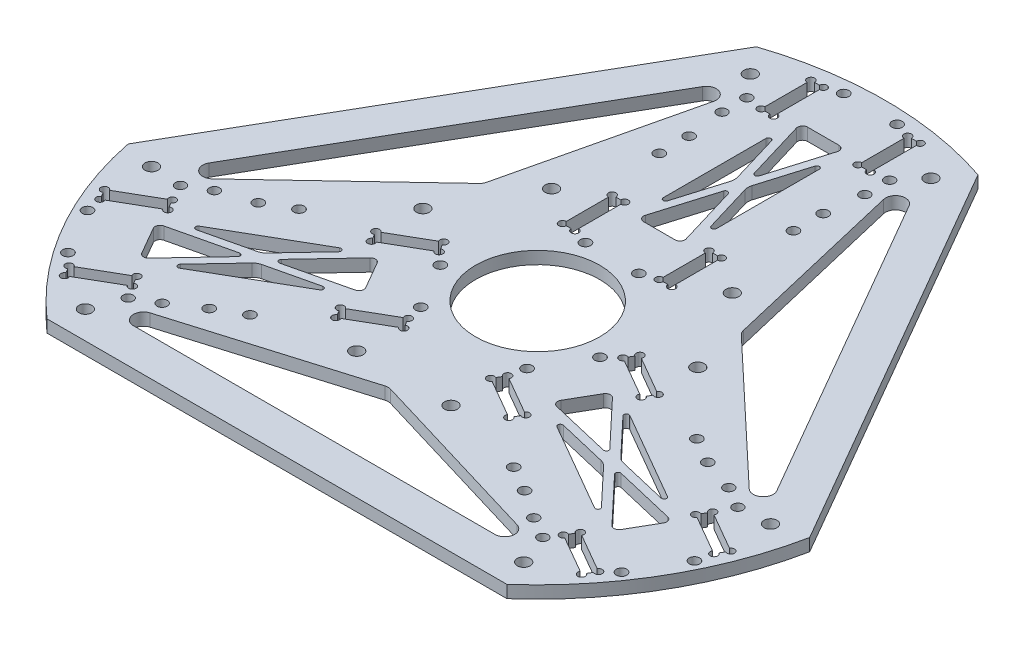
SolidWorks part; units mm, degrees
ref_plane "前视基准面" through (0, 0, 0) normal (0, 0, 1) x (1, 0, 0)
ref_plane "上视基准面" through (0, 0, 0) normal (0, 1, 0) x (1, 0, 0)
ref_plane "右视基准面" through (0, 0, 0) normal (1, 0, 0) x (0, 0, -1)
sketch "草图1" plane through (0, 0, 0) normal (0, 1, 0) x (1, 0, 0)
  line L0 (0, 0) -> (0, 50000) construction
  line L1 (0, 0) -> (-43301.2702, 25000) construction
  line L2 (-0.5416, -0.3127) -> (43300.7286, 24999.6873) construction
  line L3 (-34.641, 150) -> (-147.2243, -45)
  line L4 (34.641, 150) -> (147.2243, -45)
  line L5 (112.5833, -105) -> (-112.5833, -105)
  arc A0 (34.641, 150) -> (-34.641, 150) centre (0, 130) ccw
  arc A1 (-147.2243, -45) -> (-112.5833, -105) centre (-112.5833, -65) ccw
  arc A3 (147.2243, -45) -> (112.5833, -105) centre (112.5833, -65) cw
  dimension "D6" = 80
  dimension "D1" = 60
  dimension "D2" = 60
  dimension "D3" = 130
  dimension "D5" = 130
extrude "凸台-拉伸1" add sketch "草图1" along normal blind 5
sketch "草图2" plane through (0, 5, 0) normal (0, 1, 0) x (1, 0, 0)
  line L0 (0, 0) -> (0, 50000) construction
  line L1 (-10.75, 134) -> (-10.75, 30) construction
  line L2 (-10.75, 82) -> (49989.25, 82) construction
  line L3 (-22, 52) -> (-17, 52)
  line L4 (-22, 132) -> (-17, 132)
  line L5 (-22, 132) -> (-22, 112)
  line L6 (-22, 112) -> (-17, 112)
  line L7 (-17, 132) -> (-17, 112)
  line L8 (-17, 32) -> (-17, 52)
  line L9 (-22, 32) -> (-17, 32)
  line L10 (-22, 32) -> (-22, 52)
  line L11 (22, 32) -> (22, 52)
  line L12 (22, 32) -> (17, 32)
  line L13 (17, 32) -> (17, 52)
  line L14 (22, 52) -> (17, 52)
  line L15 (22, 112) -> (17, 112)
  line L16 (17, 132) -> (17, 112)
  line L17 (22, 132) -> (17, 132)
  line L18 (22, 132) -> (22, 112)
  circle A0 centre (-10.75, 30) radius 2.1
  circle A1 centre (-10.75, 134) radius 2.1
  circle A2 centre (10.75, 30) radius 2.1
  circle A3 centre (10.75, 134) radius 2.1
  circle A4 centre (-36.38, 42) radius 2.6
  circle A5 centre (-36.38, 122) radius 2.6
  circle A6 centre (36.38, 122) radius 2.6
  circle A7 centre (36.38, 42) radius 2.6
  circle A8 centre (-27, 88) radius 2.1
  circle A9 centre (-27, 76) radius 2.1
  circle A10 centre (27, 76) radius 2.1
  circle A11 centre (27, 88) radius 2.1
  point P15 (-10.75, 82)
  dimension "D1" = 4.2
  dimension "D6" = 5.2
  dimension "D8" = 4.2
  dimension "D2" = 21.5
  dimension "D3" = 104
  dimension "D4" = 30
  dimension "D5" = 80
  dimension "D7" = 36.38
  dimension "D9" = 27
  dimension "D10" = 6
  dimension "D11" = 5
  dimension "D12" = 5
  dimension "D13" = 20
  dimension "D14" = 30
extrude "切除-拉伸1" cut sketch "草图2" against normal blind 10
pattern_circular "阵列(圆周)1" count 3 over 360 about axis through (0, 0, 0.9148) along (0, 1, 0) of "切除-拉伸1"
sketch "草图3" plane through (0, 5, 0) normal (0, 1, 0) x (1, 0, 0)
  line L0 (-72.7463, -90) -> (72.7463, -90)
  line L1 (73.8956, -82.1687) -> (1.1494, -60.3448)
  line L2 (-1.1494, -60.3448) -> (-73.8956, -82.1687)
  line L3 (0, 0) -> (0, 50000) construction
  line L4 (-51.6854, 31.1678) -> (-34.2124, 105.0799)
  line L5 (-41.5692, 108.0001) -> (-114.3154, -18.0001)
  line L6 (-108.108, -22.9112) -> (-52.8348, 29.177)
  line L7 (52.8348, 29.177) -> (108.108, -22.9112)
  line L8 (114.3154, -18.0001) -> (41.5692, 108.0001)
  line L9 (34.2124, 105.0799) -> (51.6854, 31.1678)
  arc A0 (52.8348, 29.177) -> (51.6854, 31.1678) centre (55.5782, 32.0881) cw
  arc A1 (114.3154, -18.0001) -> (108.108, -22.9112) centre (110.8513, -20.0001) cw
  arc A2 (41.5692, 108.0001) -> (34.2124, 105.0799) centre (38.1051, 106.0001) ccw
  arc A3 (1.1494, -60.3448) -> (-1.1494, -60.3448) centre (0, -64.1761) ccw
  arc A4 (72.7463, -90) -> (73.8956, -82.1687) centre (72.7463, -86) ccw
  arc A5 (-72.7463, -90) -> (-73.8956, -82.1687) centre (-72.7463, -86) cw
  arc A6 (-108.108, -22.9112) -> (-114.3154, -18.0001) centre (-110.8513, -20.0001) cw
  arc A7 (-34.2124, 105.0799) -> (-41.5692, 108.0001) centre (-38.1051, 106.0001) ccw
  arc A8 (-51.6854, 31.1678) -> (-52.8348, 29.177) centre (-55.5782, 32.0881) cw
  point P15 (0, 0)
  point P23 (0, -60)
  point P26 (100, -90)
  point P29 (-100, -90)
  dimension "D1" = 200
  dimension "D5" = 4
  dimension "D2" = 30
  dimension "D3" = 60
  dimension "D4" = 3
extrude "切除-拉伸2" cut sketch "草图3" against normal blind 10
sketch "草图4" plane through (0, 5, 0) normal (0, 1, 0) x (1, 0, 0)
  line L0 (0, 0) -> (0, 50000) construction
  line L5 (-6.3119, 115) -> (6.3119, 115)
  line L6 (8.2276, 112.4253) -> (0.9578, 88.1928)
  line L7 (-0.9578, 88.1928) -> (-8.2276, 112.4253)
  line L8 (-10.75, 30) -> (-10.75, 134) construction
  line L9 (-10.75, 82) -> (49989.25, 82) construction
  line L10 (8.2276, 51.5747) -> (0.9578, 75.8072)
  line L11 (-6.3119, 49) -> (6.3119, 49)
  line L12 (-0.9578, 75.8072) -> (-8.2276, 51.5747)
  line L13 (-10.75, 102.6866) -> (-10.75, 61.3134)
  line L14 (-8.7922, 61.0261) -> (-2.931, 80.5633)
  line L15 (-8.7922, 102.9739) -> (-2.931, 83.4367)
  line L16 (10.75, 102.6866) -> (10.75, 61.3134)
  line L17 (8.7922, 61.0261) -> (2.931, 80.5633)
  line L18 (8.7922, 102.9739) -> (2.931, 83.4367)
  line L19 (93.5741, -43.8727) -> (73.7238, -39.18)
  line L20 (57.2462, -22.8988) -> (71.2353, -37.7433)
  line L21 (94.3042, -42.0335) -> (58.474, -21.3469)
  line L22 (40.5512, -32.9127) -> (65.1721, -38.7331)
  line L23 (66.1299, -37.0741) -> (48.7788, -18.662)
  line L24 (45.5912, -19.0337) -> (39.2793, -29.9663)
  line L25 (83.5542, -60.6531) -> (47.724, -39.9665)
  line L26 (48.4541, -38.1273) -> (68.3043, -42.82)
  line L27 (84.7819, -59.1012) -> (70.7928, -44.2567)
  line L28 (76.8561, -43.2669) -> (101.477, -49.0873)
  line L29 (102.7489, -52.0337) -> (96.437, -62.9663)
  line L30 (93.2494, -63.338) -> (75.8983, -44.9259)
  line L31 (-84.7819, -59.1012) -> (-70.7928, -44.2567)
  line L32 (-48.4541, -38.1273) -> (-68.3043, -42.82)
  line L33 (-83.5542, -60.6531) -> (-47.724, -39.9665)
  line L34 (-48.7788, -18.662) -> (-66.1299, -37.0741)
  line L35 (-65.1721, -38.7331) -> (-40.5512, -32.9127)
  line L36 (-39.2793, -29.9663) -> (-45.5912, -19.0337)
  line L37 (-94.3042, -42.0335) -> (-58.474, -21.3469)
  line L38 (-57.2462, -22.8988) -> (-71.2353, -37.7433)
  line L39 (-93.5741, -43.8727) -> (-73.7238, -39.18)
  line L40 (-75.8983, -44.9259) -> (-93.2494, -63.338)
  line L41 (-96.437, -62.9663) -> (-102.7489, -52.0337)
  line L42 (-101.477, -49.0873) -> (-76.8561, -43.2669)
  arc A0 (2.931, 80.5633) -> (2.931, 83.4367) centre (7.7202, 82) cw
  arc A1 (-2.931, 80.5633) -> (-2.931, 83.4367) centre (-7.7202, 82) ccw
  arc A2 (-10.75, 61.3134) -> (-8.7922, 61.0261) centre (-9.75, 61.3134) ccw
  arc A3 (-8.7922, 102.9739) -> (-10.75, 102.6866) centre (-9.75, 102.6866) ccw
  arc A4 (10.75, 61.3134) -> (8.7922, 61.0261) centre (9.75, 61.3134) cw
  arc A5 (10.75, 102.6866) -> (8.7922, 102.9739) centre (9.75, 102.6866) ccw
  arc A6 (0.9578, 75.8072) -> (-0.9578, 75.8072) centre (0, 75.5199) ccw
  arc A7 (0.9578, 88.1928) -> (-0.9578, 88.1928) centre (0, 88.4801) cw
  arc A8 (6.3119, 49) -> (8.2276, 51.5747) centre (6.3119, 51) ccw
  arc A9 (-6.3119, 49) -> (-8.2276, 51.5747) centre (-6.3119, 51) cw
  arc A10 (8.2276, 112.4253) -> (6.3119, 115) centre (6.3119, 113) ccw
  arc A11 (-8.2276, 112.4253) -> (-6.3119, 115) centre (-6.3119, 113) cw
  arc A12 (93.5741, -43.8727) -> (94.3042, -42.0335) centre (93.8042, -42.8995) ccw
  arc A13 (71.2353, -37.7433) -> (73.7238, -39.18) centre (74.8742, -34.3142) ccw
  arc A14 (58.474, -21.3469) -> (57.2462, -22.8988) centre (57.974, -22.213) ccw
  arc A15 (39.2793, -29.9663) -> (40.5512, -32.9127) centre (41.0113, -30.9663) ccw
  arc A16 (65.1721, -38.7331) -> (66.1299, -37.0741) centre (65.4022, -37.7599) ccw
  arc A17 (45.5912, -19.0337) -> (48.7788, -18.662) centre (47.3233, -20.0337) cw
  arc A18 (83.5542, -60.6531) -> (84.7819, -59.1012) centre (84.0542, -59.787) ccw
  arc A19 (47.724, -39.9665) -> (48.4541, -38.1273) centre (48.224, -39.1005) cw
  arc A20 (68.3043, -42.82) -> (70.7928, -44.2567) centre (67.154, -47.6858) cw
  arc A21 (101.477, -49.0873) -> (102.7489, -52.0337) centre (101.0168, -51.0337) cw
  arc A22 (75.8983, -44.9259) -> (76.8561, -43.2669) centre (76.626, -44.2401) cw
  arc A23 (93.2494, -63.338) -> (96.437, -62.9663) centre (94.7049, -61.9663) ccw
  arc A24 (-84.7819, -59.1012) -> (-83.5542, -60.6531) centre (-84.0542, -59.787) ccw
  arc A25 (-68.3043, -42.82) -> (-70.7928, -44.2567) centre (-67.154, -47.6858) ccw
  arc A26 (-47.724, -39.9665) -> (-48.4541, -38.1273) centre (-48.224, -39.1005) ccw
  arc A27 (-45.5912, -19.0337) -> (-48.7788, -18.662) centre (-47.3233, -20.0337) ccw
  arc A28 (-66.1299, -37.0741) -> (-65.1721, -38.7331) centre (-65.4022, -37.7599) ccw
  arc A29 (-39.2793, -29.9663) -> (-40.5512, -32.9127) centre (-41.0113, -30.9663) cw
  arc A30 (-94.3042, -42.0335) -> (-93.5741, -43.8727) centre (-93.8042, -42.8995) ccw
  arc A31 (-58.474, -21.3469) -> (-57.2462, -22.8988) centre (-57.974, -22.213) cw
  arc A32 (-71.2353, -37.7433) -> (-73.7238, -39.18) centre (-74.8742, -34.3142) cw
  arc A33 (-93.2494, -63.338) -> (-96.437, -62.9663) centre (-94.7049, -61.9663) cw
  arc A34 (-76.8561, -43.2669) -> (-75.8983, -44.9259) centre (-76.626, -44.2401) cw
  arc A35 (-101.477, -49.0873) -> (-102.7489, -52.0337) centre (-101.0168, -51.0337) ccw
  point P11 (-10.75, 82)
  point P25 (2.5, 82)
  point P28 (-2.5, 82)
  point P31 (-10.75, 54.5)
  point P34 (-10.75, 109.5)
  point P37 (10.75, 54.5)
  point P40 (10.75, 109.5)
  point P43 (0, 79)
  point P46 (0, 85)
  point P49 (9, 49)
  point P52 (-9, 49)
  point P55 (9, 115)
  point P58 (-9, 115)
  point P133 (0, 0)
  dimension "D5" = 5
  dimension "D6" = 1
  dimension "D7" = 2
  dimension "D1" = 30
  dimension "D2" = 3
  dimension "D3" = 18
  dimension "D4" = 55
  dimension "D8" = 3
extrude "切除-拉伸3" cut sketch "草图4" against normal blind 10
sketch "草图5" plane through (0, 0, 0) normal (0, -1, 0) x (1, 0, 0)
  circle A0 centre (0, 0) radius 25
  dimension "D1" = 50
extrude "切除-拉伸4" cut sketch "草图5" against normal blind 10
sketch "草图6" plane through (0, 5, 0) normal (0, 1, 0) x (1, 0, 0)
  line L0 (-22, 112) -> (-17, 112) construction
  line L1 (0, 135.5453) -> (0, -114.4885) construction
  line L2 (-90.8125, 82) -> (90.8125, 82) construction
  circle A0 centre (-17, 132) radius 1.5
  circle A1 centre (-22, 132) radius 1.5
  circle A2 centre (-22, 112) radius 1.5
  circle A3 centre (-17, 112) radius 1.5
  circle A4 centre (22, 132) radius 1.5
  circle A5 centre (17, 132) radius 1.5
  circle A6 centre (17, 112) radius 1.5
  circle A7 centre (22, 112) radius 1.5
  circle A8 centre (17, 32) radius 1.5
  circle A9 centre (22, 32) radius 1.5
  circle A10 centre (22, 52) radius 1.5
  circle A11 centre (17, 52) radius 1.5
  circle A12 centre (-17, 32) radius 1.5
  circle A13 centre (-22, 32) radius 1.5
  circle A14 centre (-17, 52) radius 1.5
  circle A15 centre (-22, 52) radius 1.5
  circle A16 centre (37.0051, -2.6498) radius 1.5
  circle A17 centre (39.5051, 1.6804) radius 1.5
  circle A18 centre (54.3256, -12.6498) radius 1.5
  circle A19 centre (56.8256, -8.3196) radius 1.5
  circle A20 centre (34.8256, -46.4248) radius 1.5
  circle A21 centre (17.5051, -36.4248) radius 1.5
  circle A22 centre (20.0051, -32.0946) radius 1.5
  circle A23 centre (37.3256, -42.0946) radius 1.5
  circle A24 centre (108.7871, -38.3196) radius 1.5
  circle A25 centre (106.2871, -42.6498) radius 1.5
  circle A26 centre (86.7871, -76.4248) radius 1.5
  circle A27 centre (89.2871, -72.0946) radius 1.5
  circle A28 centre (104.1076, -86.4248) radius 1.5
  circle A29 centre (106.6076, -82.0946) radius 1.5
  circle A30 centre (123.6076, -52.6498) radius 1.5
  circle A31 centre (126.1076, -48.3196) radius 1.5
  circle A32 centre (-20.0051, -32.0946) radius 1.5
  circle A33 centre (-17.5051, -36.4248) radius 1.5
  circle A34 centre (-37.3256, -42.0946) radius 1.5
  circle A35 centre (-34.8256, -46.4248) radius 1.5
  circle A36 centre (-56.8256, -8.3196) radius 1.5
  circle A37 centre (-39.5051, 1.6804) radius 1.5
  circle A38 centre (-37.0051, -2.6498) radius 1.5
  circle A39 centre (-54.3256, -12.6498) radius 1.5
  circle A40 centre (-86.7871, -76.4248) radius 1.5
  circle A41 centre (-89.2871, -72.0946) radius 1.5
  circle A42 centre (-108.7871, -38.3196) radius 1.5
  circle A43 centre (-106.2871, -42.6498) radius 1.5
  circle A44 centre (-126.1076, -48.3196) radius 1.5
  circle A45 centre (-123.6076, -52.6498) radius 1.5
  circle A46 centre (-106.6076, -82.0946) radius 1.5
  circle A47 centre (-104.1076, -86.4248) radius 1.5
  point P13 (0, 82)
  point P109 (0, -0.9148)
  dimension "D1" = 3
  dimension "D5" = 20
  dimension "D4" = 30
  dimension "D2" = 2
  dimension "D3" = 2
  dimension "D6" = 3
extrude "切除-拉伸5" cut sketch "草图6" against normal through all
sketch "草图7" plane through (0, 5, 0) normal (0, 1, 0) x (1, 0, 0)
  line L0 (-134.8938, 37.4655) -> (-181.0921, -128.8703)
  line L1 (-181.0921, -128.8703) -> (-73.5197, -119.1422)
  line L2 (13.579, -139.3399) -> (224.5167, -118.7835)
  line L3 (224.5167, -118.7835) -> (140, 0)
  line L4 (104.2307, 93.4664) -> (0, 209.701)
  line L5 (0, 209.701) -> (-104.2307, 93.4664)
  circle A0 centre (0, 0) radius 140
  dimension "D1" = 280
extrude "切除-拉伸6" cut sketch "草图7" against normal through all contours A0 L4 L5 | A0 L0 L1 | A0 L2 L3
sketch "草图8" plane through (0, 5, 0) normal (0, 1, 0) x (1, 0, 0)
  line L0 (-10.75, 102.6866) -> (-10.75, 61.3134) construction
  line L1 (0, 140) -> (0, 25.9366) construction
  circle A0 centre (-28.75, 103) radius 2.05
  circle A2 centre (-27, 88) radius 2.1 construction
  circle A3 centre (-28.75, 113) radius 2.05
  arc A4 (44.632, 132.6951) -> (-44.632, 132.6951) centre (0, 0) ccw construction
  circle A5 centre (28.75, 103) radius 2.05
  circle A6 centre (28.75, 113) radius 2.05
  circle A7 centre (112.2359, -31.6018) radius 2.05
  circle A8 centre (103.5756, -26.6018) radius 2.05
  circle A9 centre (83.4859, -81.3982) radius 2.05
  circle A10 centre (74.8256, -76.3982) radius 2.05
  circle A11 centre (-83.4859, -81.3982) radius 2.05
  circle A12 centre (-74.8256, -76.3982) radius 2.05
  circle A13 centre (-112.2359, -31.6018) radius 2.05
  circle A14 centre (-103.5756, -26.6018) radius 2.05
  point P38 (0, 0)
  dimension "D1" = 18
  dimension "D2" = 4.1
  dimension "D3" = 15
  dimension "D5" = 10
  dimension "D6" = 3
  dimension "D4" = 2
extrude "切除-拉伸7" cut sketch "草图8" against normal blind 10
